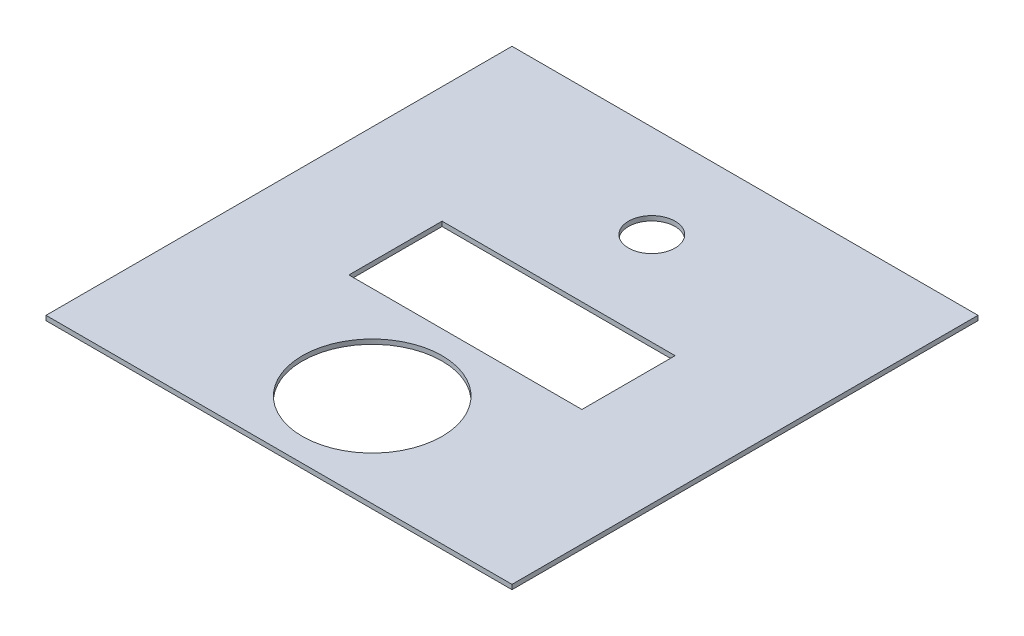
SolidWorks part; units mm, degrees
ref_plane "Front Plane" through (0, 0, 0) normal (0, 0, 1) x (1, 0, 0)
ref_plane "Top Plane" through (0, 0, 0) normal (0, 1, 0) x (1, 0, 0)
ref_plane "Right Plane" through (0, 0, 0) normal (1, 0, 0) x (0, 0, -1)
sketch "Sketch1" plane through (0, 0, 0) normal (0, 1, 0) x (1, 0, 0)
  line L1 (-50, -50) -> (50, -50)
  line L2 (-50, -50) -> (-50, 50)
  line L3 (-50, 50) -> (50, 50)
  line L4 (50, -50) -> (50, 50)
  line L5 (-50, -50) -> (50, 50) construction
  line L6 (-50, 50) -> (50, -50) construction
  point P0 (0, 0)
  dimension "D1" = 100
  dimension "D2" = 100
extrude "Boss-Extrude1" add sketch "Sketch1" along normal blind 1
sketch "Sketch2" plane through (0, 1, 0) normal (0, 1, 0) x (1, 0, 0)
  line L1 (-25, -10) -> (25, -10)
  line L2 (-25, -10) -> (-25, 10)
  line L3 (-25, 10) -> (25, 10)
  line L4 (25, -10) -> (25, 10)
  line L5 (-25, -10) -> (25, 10) construction
  line L6 (-25, 10) -> (25, -10) construction
  point P0 (0, 0)
  dimension "D1" = 50
  dimension "D2" = 20
extrude "Cut-Extrude1" cut sketch "Sketch2" against normal blind 1
sketch "Sketch3" plane through (0, 1, 0) normal (0, 1, 0) x (1, 0, 0)
  circle A0 centre (0, 30) radius 5
  circle A1 centre (0, -30) radius 15
  point P4 (0, 0)
  dimension "D3" = 10
  dimension "D4" = 30
  dimension "D1" = 30
  dimension "D2" = 30
extrude "Cut-Extrude2" cut sketch "Sketch3" against normal up to vertex (1 mm away) up to point (0, 0, 0)
